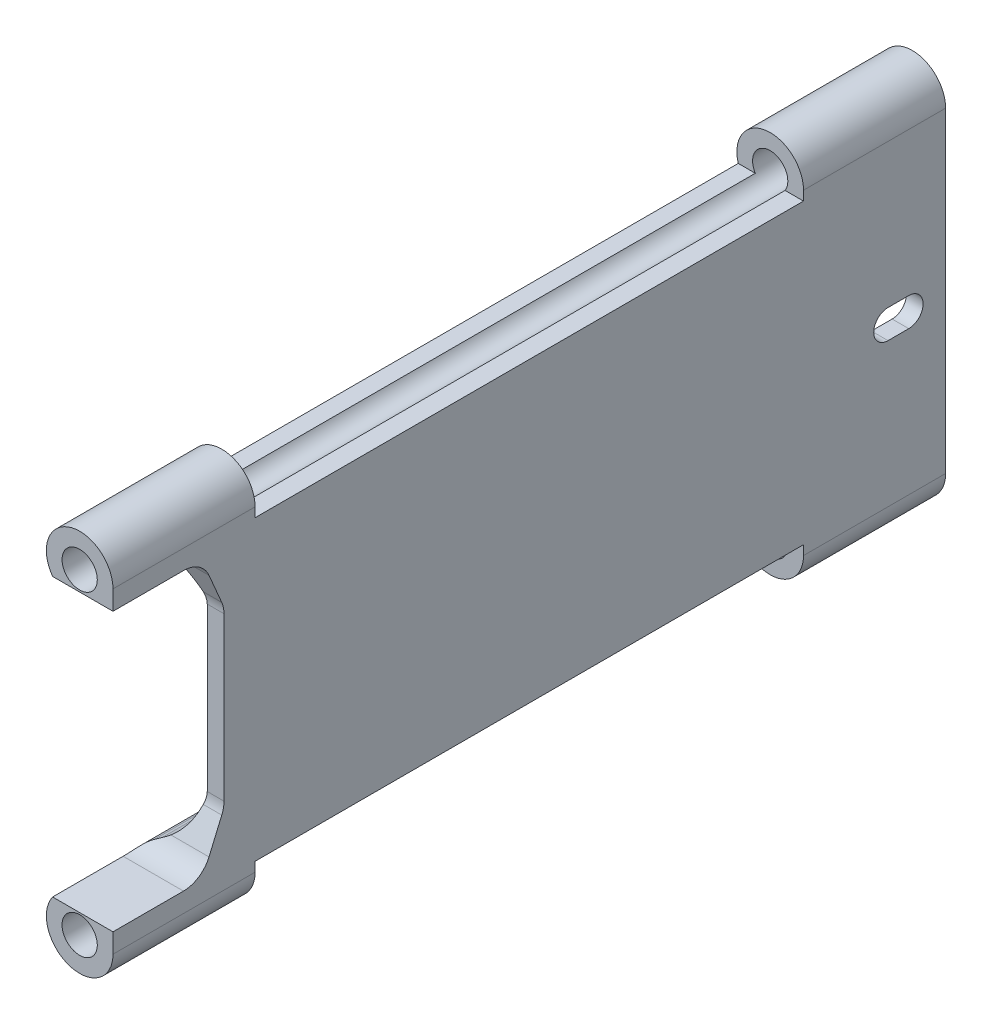
SolidWorks part; units mm, degrees
material "ABS"
ref_plane "Alzado" through (0, 0, 0) normal (0, 0, 1) x (1, 0, 0)
ref_plane "Planta" through (0, 0, 0) normal (0, 1, 0) x (1, 0, 0)
ref_plane "Vista lateral" through (0, 0, 0) normal (1, 0, 0) x (0, 0, -1)
sketch "Croquis1" plane through (0, 0, 0) normal (0, 0, 1) x (1, 0, 0)
  line L5 (-13.465, 0) -> (13.8234, 0) construction
  line L8 (-3, 19.8598) -> (-8.9869, 23.2963)
  line L9 (-3, 19.8598) -> (-3, -19.8598)
  line L10 (0, 28.5) -> (0, -28.5)
  line L11 (-3, -19.8598) -> (-8.9869, -23.2963)
  circle A0 centre (-6, 28.5) radius 3.175
  arc A5 (0, 28.5) -> (-8.9869, 23.2963) centre (-6, 28.5) ccw
  arc A6 (0, -28.5) -> (-8.9869, -23.2963) centre (-6, -28.5) cw
  circle A7 centre (-6, -28.5) radius 3.175
  point P7 (0, 0)
  point P15 (0, 0)
  point P16 (-3, 0)
  point P17 (-3, 0)
  dimension "D1" = 6.35
  dimension "D2" = 57
  dimension "D3" = 3
  dimension "D4" = 6
extrude "Saliente-Extruir1" add sketch "Croquis1" against normal blind 150
fillet "Redondeo1" radius 10 2 edges at (-3, -19.8598, -75) (-3, 19.8598, -75)
sketch "Croquis2" plane through (0, 0, 0) normal (1, 0, 0) x (0, 0, -1)
  line L0 (16, 25) -> (20, 15.6468)
  line L1 (20, 15.6468) -> (20, -15.6468)
  line L2 (-29.8735, 0) -> (35.3957, 0) construction
  line L3 (16, 25) -> (-29.8735, 25)
  line L4 (-29.8735, 25) -> (-29.8735, -25)
  line L5 (16, -25) -> (-29.8735, -25)
  line L6 (16, -25) -> (20, -15.6468)
  line L8 (0, -28.5) -> (0, 28.5) construction
  point P10 (20, 0)
  dimension "D1" = 50
  dimension "D2" = 16
  dimension "D3" = 20
extrude "Cortar-Extruir1" cut sketch "Croquis2" against normal through all
fillet "Redondeo2" radius 5 4 edges at (-1.5626, 15.6468, -20) (-1.5626, -15.6468, -20) (-5.4367, -25, -16) (-5.4367, 25, -16)
sketch "Croquis3" plane through (0, 0, 0) normal (1, 0, 0) x (0, 0, -1)
  line L0 (0, 0) -> (150, 0) construction
  line L1 (25.6041, 44.9478) -> (124.3959, 44.9478)
  line L2 (25.6041, 44.9478) -> (25.6041, 26.8024)
  line L3 (25.6041, 26.8024) -> (124.3959, 26.8024)
  line L4 (124.3959, 44.9478) -> (124.3959, 26.8024)
  line L5 (124.3959, -44.9478) -> (124.3959, -26.8024)
  line L6 (25.6041, -26.8024) -> (124.3959, -26.8024)
  line L7 (25.6041, -44.9478) -> (25.6041, -26.8024)
  line L8 (25.6041, -44.9478) -> (124.3959, -44.9478)
  line L9 (150, 14.0695) -> (150, -14.0695) construction
  point P16 (75, 0)
  point P17 (75, -26.8024)
extrude "Cortar-Extruir2" cut sketch "Croquis3" against normal through all
sketch "Croquis4" plane through (-3, 0, 0) normal (-1, 0, 0) x (0, 0, 1)
  line L0 (-143.3598, 0) -> (-139.6272, 0) construction
  line L1 (-143.3598, 2.5791) -> (-139.6272, 2.5791)
  line L2 (-143.3598, -2.5791) -> (-139.6272, -2.5791)
  arc A0 (-143.3598, 2.5791) -> (-143.3598, -2.5791) centre (-143.3598, 0) ccw
  arc A1 (-139.6272, -2.5791) -> (-139.6272, 2.5791) centre (-139.6272, 0) ccw
  point P2 (-141.4935, 0)
  point P8 (-142.5656, 0)
  point P9 (-143.3598, 0)
extrude "Cortar-Extruir3" cut sketch "Croquis4" against normal through all
